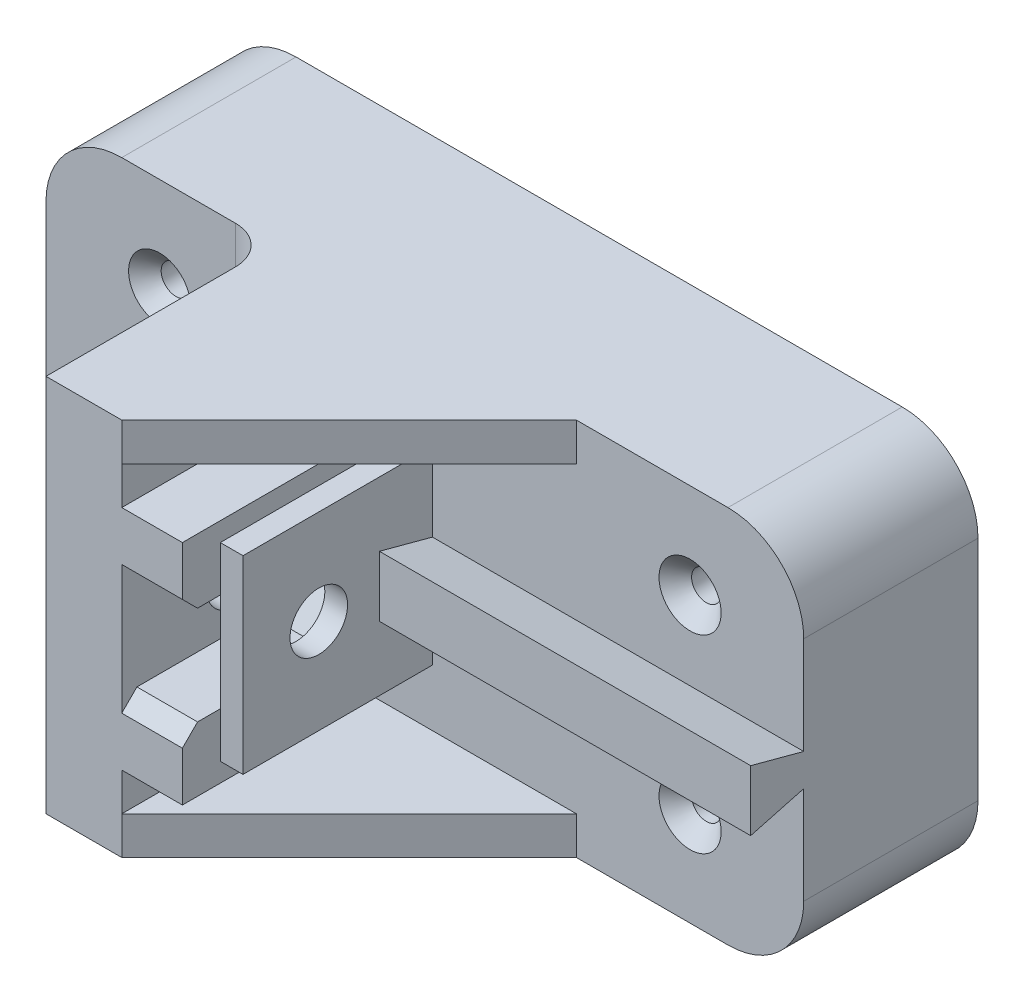
SolidWorks part; units mm, degrees
ref_plane "Piano frontale" through (0, 0, 0) normal (1, 0, 0) x (0, 1, 0)
ref_plane "Piano superiore" through (0, 0, 0) normal (0, 0, 1) x (0, 1, 0)
ref_plane "Piano destro" through (0, 0, 0) normal (0, 1, 0) x (-1, 0, 0)
sketch "Schizzo1" plane through (0, 0, 0) normal (1, 0, 0) x (0, 1, 0)
  line L1 (-25, 23) -> (25, 23)
  line L2 (-25, 23) -> (-25, 0)
  line L3 (-25, 0) -> (25, 0)
  line L4 (25, 23) -> (25, 0)
  dimension "D1" = 23
  dimension "D2" = 50
extrude "Estrusione-Estrusione1" add sketch "Schizzo1" along normal blind 100
sketch "Schizzo2" plane through (0, 0, 23) normal (0, 0, 1) x (1, 0, 0)
  line L0 (100, 25) -> (0, 25) construction
  line L1 (30, 25) -> (40, 25)
  line L2 (30, 25) -> (30, -25)
  line L3 (30, -25) -> (40, -25)
  line L4 (40, 25) -> (40, -25)
  line L5 (100, -25) -> (0, -25) construction
  line L6 (0, 25) -> (0, -25) construction
  dimension "D1" = 10
  dimension "D2" = 30
extrude "Estrusione-Estrusione2" add sketch "Schizzo2" along normal blind 30
hole_wizard "M7 Clearance Hole1" positions "Schizzo3" profile "Schizzo4" hole size "M7" standard "ANSI Metric" end condition through all
sketch "Schizzo3" plane through (30, 0, 0) normal (-1, 0, 0) x (0, 0, 1)
  line L0 (23, 25) -> (53, -25) construction
  point P6 (38, 0)
sketch "Schizzo4" plane through (30, 0, 38) normal (0, 1, 0) x (0, 0, 1)
  line L0 (0, 0) -> (0, 70)
  line L1 (0, 70) -> (3.8, 70)
  line L2 (3.8, 70) -> (3.8, 0)
  line L5 (3.8, 0) -> (0, 0)
  line L11 (0, -6.35) -> (0, 107.95) construction
  dimension "Thru Hole Dia." = 7.6
  dimension "Thru Hole Depth" = 70
sketch "Schizzo5" plane through (40, 0, 0) normal (1, 0, 0) x (0, 1, 0)
  line L0 (-25, 23) -> (25, 23) construction
  line L1 (-2.1244, 23) -> (2.1244, 23)
  line L12 (2.1244, 23) -> (4, 30)
  line L13 (4, 30) -> (-4, 30)
  line L14 (-4, 30) -> (-2.1244, 23)
  line L15 (0, 30) -> (0, 23) construction
  point P8 (0, 23)
  dimension "D1" = 75
  dimension "D2" = 7
  dimension "D3" = 8
extrude "Estrusione-Estrusione3" add sketch "Schizzo5" along normal up to surface (60 mm away) up to face at (100, 0, 11.5)
sketch "Schizzo10" plane through (0, -25, 0) normal (0, -1, 0) x (1, 0, 0)
  line L0 (40, 53) -> (70, 23)
  line L1 (100, 23) -> (40, 23) construction
  dimension "D1" = 45
rib "Nervatura2" sketch "Schizzo10" sketch "Schizzo10" thickness 5 extrusion direction parallel to sketch draft on no parameters "D1"=5
mirror "Specchia2" about plane through (0, 0, 0) normal (0, 1, 0) of "Nervatura2"
sketch "Schizzo11" plane through (40, 0, 0) normal (1, 0, 0) x (0, 1, 0)
  line L0 (-2.1244, 23) -> (-25, 23) construction
  line L1 (-15, 23) -> (15, 23)
  line L2 (-15, 23) -> (-15, 53)
  line L3 (-15, 53) -> (15, 53)
  line L4 (15, 23) -> (15, 53)
  line L5 (0, -29.15) -> (0, 29.15) construction
  point P6 (0, 23)
  dimension "D1" = 30
  dimension "D2" = 30
extrude "Estrusione-Estrusione4" add sketch "Schizzo11" along normal blind 8 contours L2 L3 L4 L1
sketch "Schizzo13" plane through (48, 0, 0) normal (1, 0, 0) x (0, 1, 0)
  line L0 (-15, 23) -> (-15, 53) construction
  line L1 (6.5, 41.7528) -> (0, 45.5056) construction
  line L2 (0, 45.5056) -> (-6.5, 41.7528) construction
  line L3 (-6.5, 41.7528) -> (-6.5, 34.2472)
  line L4 (-6.5, 34.2472) -> (0, 30.4944)
  line L5 (0, 30.4944) -> (6.5, 34.2472)
  line L6 (6.5, 34.2472) -> (6.5, 41.7528)
  line L7 (-15, 53) -> (15, 53) construction
  line L8 (6.5, 41.7528) -> (-6.5, 41.7528) construction
  line L9 (6.5, 41.7528) -> (6.5, 53)
  line L10 (6.5, 53) -> (-6.5, 53)
  line L11 (-6.5, 41.7528) -> (-6.5, 53)
  circle A0 centre (0, 38) radius 6.5 construction
  circle A1 centre (0, 38) radius 3.8 construction
  dimension "D1" = 13
extrude "Taglio-Estrusione1" cut sketch "Schizzo13" against normal up to surface (8 mm away) up to face at (40, -17.5, 38)
ref_plane "Plane1" through (0, 0, 10) normal (0, 0, 1) x (1, 0, 0)
hole_wizard "CSK for M3.5 Oval Head Machine Screw1" positions "Schizzo14" profile "Schizzo16" countersink size "M3.5" standard "ANSI Metric"
sketch "Schizzo14" plane through (0, 0, 23) normal (0, 0, 1) x (1, 0, 0)
  line L2 (30, -25) -> (0, 0) construction
  point P14 (15, -12.5)
sketch "Schizzo16" plane through (15, -12.5, 23) normal (1, 0, 0) x (0, -1, 0)
  line L0 (0, 0) -> (0, 31.1717)
  line L1 (0, 31.1717) -> (1.95, 30)
  line L2 (1.95, 30) -> (1.95, 2.15)
  line L3 (1.95, 2.15) -> (4.1, 0)
  line L5 (4.1, 0) -> (0, 0)
  line L6 (-1.95, 2.15) -> (-4.1, 0) construction
  line L10 (0, 31.1717) -> (-1.95, 30) construction
  line L11 (0, -6.35) -> (0, 107.95) construction
  dimension "Hole Dia." = 3.9
  dimension "Hole Depth" = 30
  dimension "Near C'Sink Dia." = 8.2
  dimension "Near C'Sink Angle" = 90
  dimension "Drill Angle" = 118
ref_plane "Piano2" through (50, 0, 0) normal (-1, 0, 0) x (0, 0, 1)
mirror "Specchia3" about plane through (50, 0, 0) normal (-1, 0, 0) of "CSK for M3.5 Oval Head Machine Screw1" second plane through (0, 0, 0) second plane normal (0, 1, 0)
fillet "Raccordo1" radius 10 4 edges at (100, -25, 11.5) (0, -25, 11.5) (0, 25, 11.5) (100, 25, 11.5)
chamfer "Smusso2" distance 2 angle 45 2 edges at (44, 6.5, 53) (44, -6.5, 53)
fillet "Raccordo2" radius 5 1 edges at (30, 0, 23)
sketch "Schizzo17" plane through (48, 0, 0) normal (1, 0, 0) x (0, 1, 0)
  line L0 (2.1244, 23) -> (15, 23) construction
  line L1 (-12.5, 23) -> (12.5, 23)
  line L2 (-12.5, 23) -> (-12.5, 48)
  line L3 (-12.5, 48) -> (12.5, 48)
  line L4 (12.5, 23) -> (12.5, 48)
  line L5 (-12.5, 23) -> (12.5, 48) construction
  line L6 (-12.5, 48) -> (12.5, 23) construction
  point P0 (0, 35.5)
  point P5 (0, 0)
  point P6 (0, 38)
  point P7 (0, 38)
  point P8 (0, 41.5212)
  point P9 (7.2849, 35.6965)
  point P10 (7.6738, 34.5988)
  point P11 (0, 0)
  point P14 (10.0562, 37.9806)
  point P15 (0, 23)
  point P17 (0, 0)
  point P18 (6.5, 47.4157)
  point P19 (8.0686, 48)
  point P21 (0, 0)
  dimension "D1" = 25
  dimension "D2" = 25
extrude "Estrusione-Estrusione8" add sketch "Schizzo17" along normal blind 3 contours L3 L4 L1 L2
hole_wizard "M7 Clearance Hole2" positions "Schizzo18" profile "Schizzo19" hole size "M7" standard "ANSI Metric" end condition through all
sketch "Schizzo18" plane through (51, 0, 0) normal (1, 0, 0) x (0, 0, -1)
  circle A0 centre (-38, 0) radius 3.8 construction
  circle A1 centre (-38, 0) radius 3.8 construction
  point P0 (-38, 0)
  point P3 (0, 0)
  point P7 (0, 0)
sketch "Schizzo19" plane through (51, 0, 38) normal (0, 1, 0) x (0, 0, -1)
  line L0 (0, 0) -> (0, 51)
  line L1 (0, 51) -> (3.8, 51)
  line L2 (3.8, 51) -> (3.8, 0)
  line L5 (3.8, 0) -> (0, 0)
  line L11 (0, -6.35) -> (0, 107.95) construction
  dimension "Thru Hole Dia." = 7.6
  dimension "Thru Hole Depth" = 51
